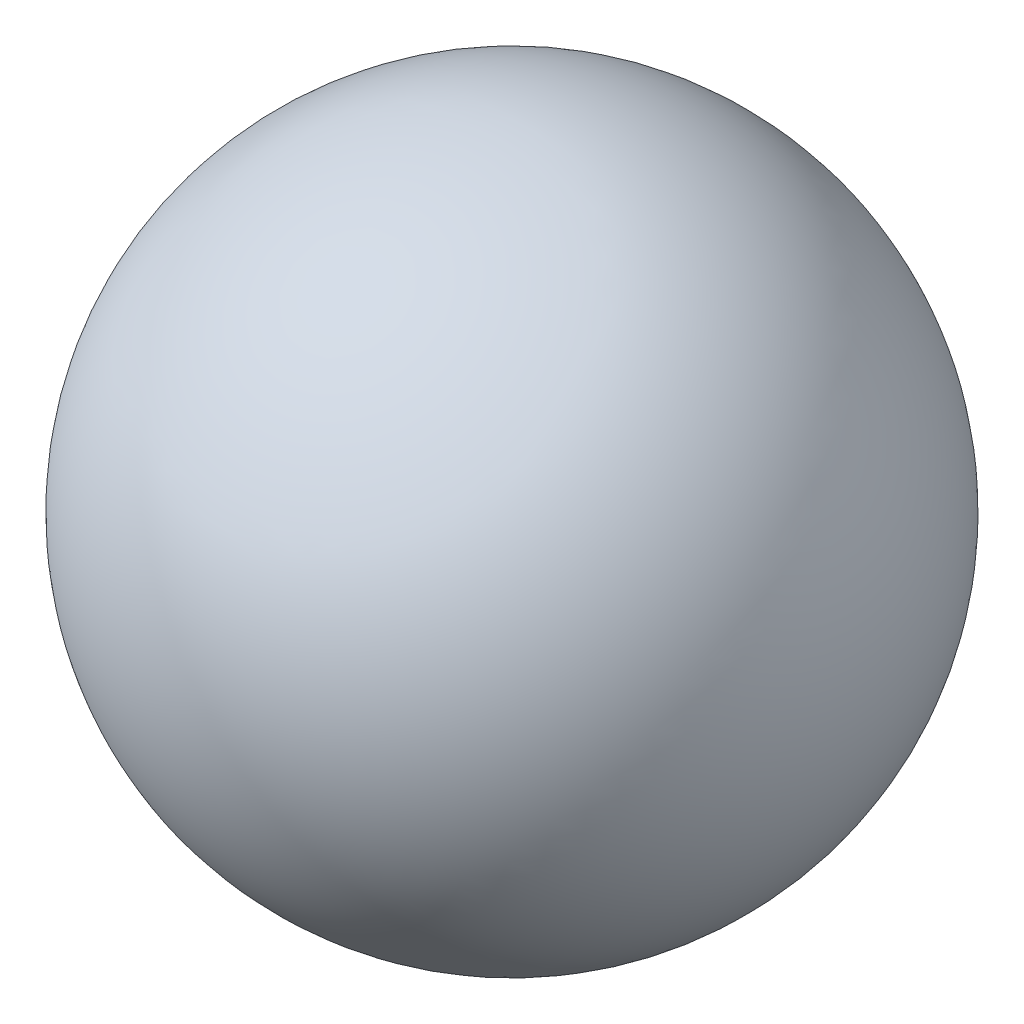
SolidWorks part; units mm, degrees
ref_plane "前视基准面" through (0, 0, 0) normal (0, 0, 1) x (1, 0, 0)
ref_plane "上视基准面" through (0, 0, 0) normal (0, 1, 0) x (1, 0, 0)
ref_plane "右视基准面" through (0, 0, 0) normal (1, 0, 0) x (0, 0, -1)
sketch "草图1" plane through (0, 0, 0) normal (0, 1, 0) x (1, 0, 0)
  line L0 (0, 5.1) -> (0, -5.1)
  arc A0 (0, -5.1) -> (0, 5.1) centre (0, 0) ccw
revolve "旋转1" add sketch "草图1" angle 360 about L0
